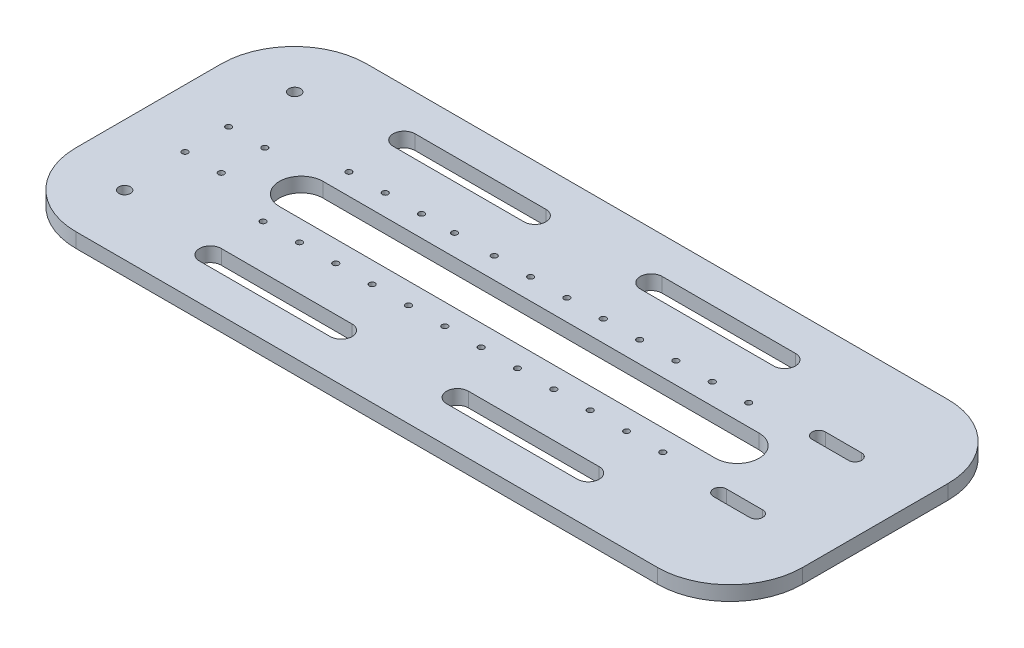
SolidWorks part; units mm, degrees
ref_plane "Front Plane" through (0, 0, 0) normal (0, 0, 1) x (1, 0, 0)
ref_plane "Top Plane" through (0, 0, 0) normal (0, 1, 0) x (1, 0, 0)
ref_plane "Right Plane" through (0, 0, 0) normal (1, 0, 0) x (0, 0, -1)
sketch "Sketch1" plane through (0, 0, 0) normal (0, 1, 0) x (1, 0, 0)
  line L1 (0, 0) -> (500, 0)
  line L2 (0, 0) -> (0, 200)
  line L3 (0, 200) -> (500, 200)
  line L4 (500, 0) -> (500, 200)
  dimension "D1" = 500
  dimension "D2" = 200
extrude "Boss-Extrude1" add sketch "Sketch1" along normal blind 10
fillet "Fillet1" radius 50 4 edges at (500, 5, -200) (500, 5, 0) (0, 5, -200) (0, 5, 0)
sketch "Sketch2" plane through (0, 10, 0) normal (0, 1, 0) x (1, 0, 0)
  line L0 (105, 115) -> (405, 115)
  line L1 (105, 85) -> (405, 85)
  line L2 (500, 50) -> (500, 150) construction
  line L3 (50, 0) -> (450, 0) construction
  line L4 (427, 138.5) -> (452, 138.5)
  line L5 (427, 129.5) -> (452, 129.5)
  line L6 (427, 70.5) -> (452, 70.5)
  line L7 (427, 61.5) -> (452, 61.5)
  line L8 (434.2651, 70.5) -> (105, 70.5) construction
  line L9 (435.2345, 129.5) -> (102.7241, 129.5) construction
  line L10 (65, 115) -> (65, 85) construction
  line L11 (40, 115) -> (40, 85) construction
  line L12 (105, 115) -> (105, 85) construction
  line L13 (108.2748, 160) -> (198.2748, 160)
  line L14 (108.2748, 175) -> (198.2748, 175)
  line L15 (278.2748, 160) -> (370, 160)
  line L16 (278.2748, 175) -> (370, 175)
  line L17 (110, 25) -> (200, 25)
  line L18 (110, 40) -> (200, 40)
  line L19 (280, 25) -> (370, 25)
  line L20 (280, 40) -> (370, 40)
  line L21 (450, 200) -> (50, 200) construction
  circle A2 centre (42, 41.5) radius 4
  circle A3 centre (42, 158.5) radius 4
  arc A5 (105, 115) -> (105, 85) centre (105, 100) ccw
  arc A6 (405, 115) -> (405, 85) centre (405, 100) cw
  arc A7 (427, 138.5) -> (427, 129.5) centre (427, 134) ccw
  arc A8 (452, 138.5) -> (452, 129.5) centre (452, 134) cw
  arc A9 (427, 70.5) -> (427, 61.5) centre (427, 66) ccw
  arc A10 (452, 70.5) -> (452, 61.5) centre (452, 66) cw
  circle A23 centre (108.2748, 70.5) radius 2
  circle A24 centre (133.2748, 70.5) radius 2
  circle A25 centre (158.2748, 70.5) radius 2
  circle A26 centre (183.2748, 70.5) radius 2
  circle A27 centre (208.2748, 70.5) radius 2
  circle A28 centre (233.2748, 70.5) radius 2
  circle A29 centre (258.2748, 70.5) radius 2
  circle A30 centre (283.2748, 70.5) radius 2
  circle A31 centre (308.2748, 70.5) radius 2
  circle A32 centre (333.2748, 70.5) radius 2
  circle A33 centre (358.2748, 70.5) radius 2
  circle A34 centre (383.2748, 70.5) radius 2
  circle A35 centre (133.2748, 129.5) radius 2
  circle A36 centre (158.2748, 129.5) radius 2
  circle A37 centre (180.999, 129.5) radius 2
  circle A38 centre (208.2748, 129.5) radius 2
  circle A39 centre (233.2748, 129.5) radius 2
  circle A40 centre (258.2748, 129.5) radius 2
  circle A41 centre (283.2748, 129.5) radius 2
  circle A42 centre (308.2748, 129.5) radius 2
  circle A43 centre (333.2748, 129.5) radius 2
  circle A44 centre (358.2748, 129.5) radius 2
  circle A45 centre (383.2748, 129.5) radius 2
  circle A46 centre (108.2748, 129.5) radius 2
  circle A47 centre (40, 115) radius 2
  circle A48 centre (65, 115) radius 2
  circle A49 centre (65, 85) radius 2
  circle A50 centre (40, 85) radius 2
  arc A51 (108.2748, 175) -> (108.2748, 160) centre (108.2748, 167.5) ccw
  arc A52 (198.2748, 175) -> (198.2748, 160) centre (198.2748, 167.5) cw
  arc A53 (278.2748, 175) -> (278.2748, 160) centre (278.2748, 167.5) ccw
  arc A54 (370, 175) -> (370, 160) centre (370, 167.5) cw
  arc A55 (110, 40) -> (110, 25) centre (110, 32.5) ccw
  arc A56 (200, 40) -> (200, 25) centre (200, 32.5) cw
  arc A57 (280, 40) -> (280, 25) centre (280, 32.5) ccw
  arc A58 (370, 40) -> (370, 25) centre (370, 32.5) cw
  dimension "D1" = 85
  dimension "D4" = 117
  dimension "D5" = 8
  dimension "D6" = 8
  dimension "D13" = 48
  dimension "D14" = 48
  dimension "D26" = 41.5
  dimension "D9" = 4
  dimension "D17" = 4
  dimension "D18" = 40
  dimension "D2" = 30
  dimension "D3" = 25
  dimension "D7" = 25
  dimension "D8" = 77
  dimension "D10" = 9
  dimension "D11" = 300
  dimension "D12" = 95
  dimension "D15" = 385
  dimension "D16" = 9
  dimension "D19" = 25
  dimension "D20" = 90
  dimension "D21" = 15
  dimension "D22" = 25
  dimension "D23" = 25
  dimension "D24" = 25
  dimension "D25" = 61.5
  dimension "D27" = 25
  dimension "D28" = 130
  dimension "D29" = 130
  dimension "D30" = 80
  dimension "D31" = 80
extrude "Cut-Extrude2" cut sketch "Sketch2" against normal blind 10
